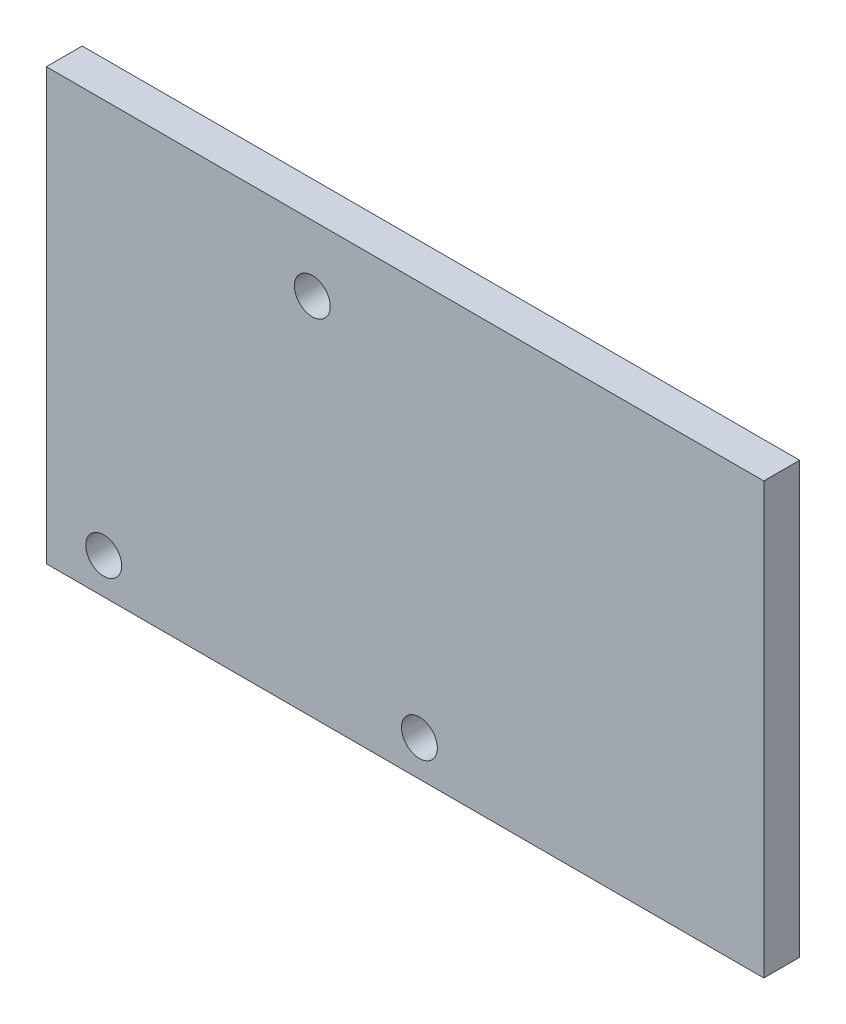
SolidWorks part; units mm, degrees
material "ABS"
ref_plane "Front Plane" through (0, 0, 0) normal (0, 0, 1) x (1, 0, 0)
ref_plane "Top Plane" through (0, 0, 0) normal (0, 1, 0) x (1, 0, 0)
ref_plane "Right Plane" through (0, 0, 0) normal (1, 0, 0) x (0, 0, -1)
sketch "Sketch1" plane through (0, 0, 0) normal (0, 0, 1) x (1, 0, 0)
  line L1 (0, 0) -> (-127, 0)
  line L2 (0, 0) -> (0, 76.2)
  line L3 (0, 76.2) -> (-127, 76.2)
  line L4 (-127, 0) -> (-127, 76.2)
  dimension "D1" = 76.2
  dimension "D2" = 127
extrude "Boss-Extrude1" add sketch "Sketch1" along normal blind 6.35
sketch "Sketch4" plane through (0, 0, 0) normal (0, 0, -1) x (-1, 0, 0)
  circle A0 centre (79.9125, 64.573) radius 3.175
  dimension "D1" = 6.35
extrude "Cut-Extrude1" cut sketch "Sketch4" against normal through all both and the other way through all
hole_wizard "1/4 (0.25) Diameter Hole1" positions "Sketch6" profile "Sketch8" hole size "1/4" standard "ANSI Inch" end condition through all
sketch "Sketch6" plane through (0, 0, 0) normal (0, 0, -1) x (-1, 0, 0)
  line L0 (127, 76.2) -> (127, 0) construction
  line L1 (127, 0) -> (0, 0) construction
  line L2 (50.8, 12.7) -> (50.8, 0) construction
  point P0 (116.84, 6.35)
  point P2 (60.96, 6.35)
  dimension "D1" = 10.16
  dimension "D2" = 6.35
  dimension "D3" = 6.35
  dimension "D4" = 10.16
sketch "Sketch8" plane through (-116.84, 6.35, 0) normal (1, 0, 0) x (0, 1, 0)
  line L0 (0, 0) -> (0, 6.35)
  line L1 (0, 6.35) -> (3.175, 6.35)
  line L2 (3.175, 6.35) -> (3.175, 0.635)
  line L3 (3.175, 0.635) -> (3.81, 0)
  line L5 (3.81, 0) -> (0, 0)
  line L6 (-3.175, 0.635) -> (-3.81, 0) construction
  line L11 (0, -6.35) -> (0, 107.95) construction
  dimension "Thru Hole Dia." = 6.35
  dimension "Thru Hole Depth" = 6.35
  dimension "Near C'Sink Dia." = 7.62
  dimension "Near C'Sink Angle" = 90
